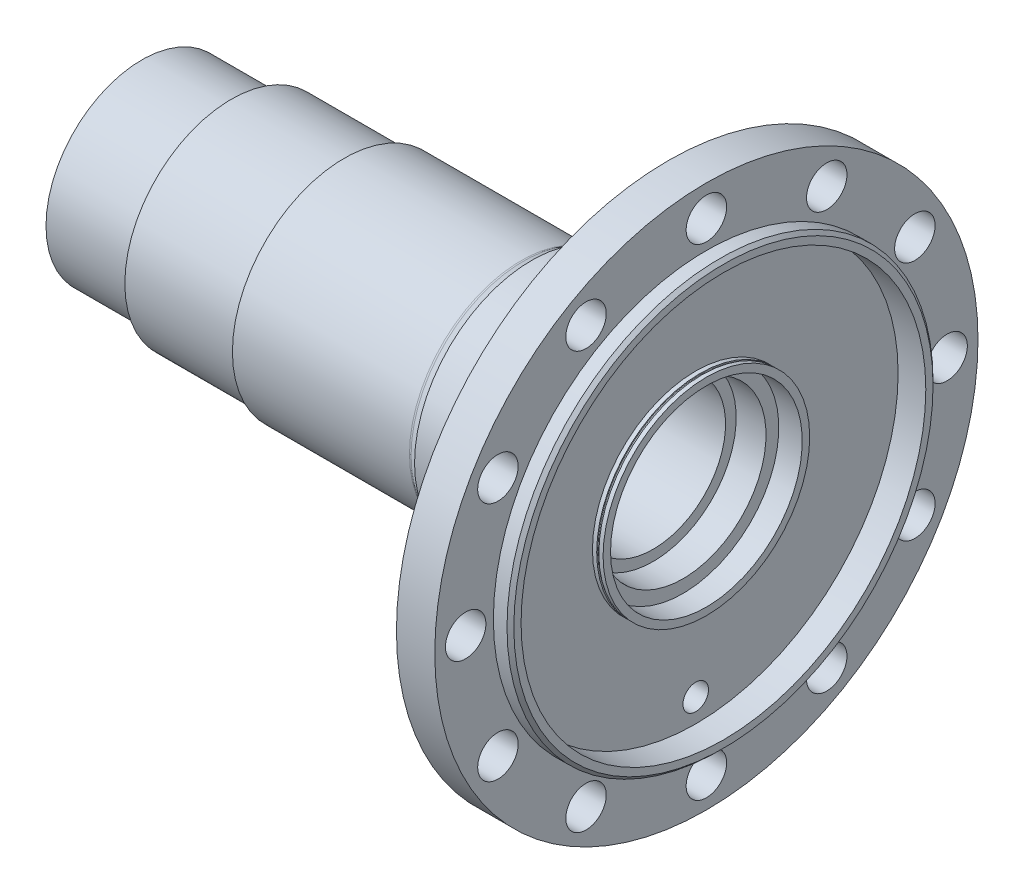
SolidWorks part; units mm, degrees
ref_plane "Спереди" through (0, 0, 0) normal (0, 0, 1) x (1, 0, 0)
ref_plane "Сверху" through (0, 0, 0) normal (0, 1, 0) x (1, 0, 0)
ref_plane "Справа" through (0, 0, 0) normal (1, 0, 0) x (0, 0, -1)
sketch "Эскиз1" plane through (0, 0, 0) normal (0, 0, 1) x (1, 0, 0)
  line L0 (0, 0) -> (273, 0)
  line L1 (0, 0) -> (0, 45)
  line L2 (0, 45) -> (42, 45)
  line L3 (42, 45) -> (42, 50)
  line L4 (42, 50) -> (95, 50)
  line L5 (95, 50) -> (95, 52.5)
  line L6 (95, 52.5) -> (178.134, 52.5)
  line L7 (179.134, 52.7679) -> (183, 55)
  line L8 (183, 55) -> (213, 55)
  line L9 (215, 57) -> (215, 60.7679)
  line L10 (215, 60.7679) -> (218, 62.5)
  line L11 (218, 62.5) -> (237, 62.5)
  line L12 (239, 64.5) -> (239, 100)
  line L13 (239, 100) -> (247, 100)
  line L14 (247, 100) -> (247, 127.5)
  line L15 (247, 127.5) -> (265, 127.5)
  line L16 (265, 127.5) -> (265, 100)
  line L17 (265, 100) -> (271.4, 100)
  line L18 (271.4, 100) -> (273, 98.4)
  line L19 (273, 98.4) -> (273, 0)
  arc A0 (178.134, 52.5) -> (179.134, 52.7679) centre (178.134, 54.5) ccw
  arc A1 (213, 55) -> (215, 57) centre (213, 57) ccw
  arc A2 (237, 62.5) -> (239, 64.5) centre (237, 64.5) ccw
revolve "Повернуть1" add sketch "Эскиз1" angle 360 about L0
sketch "Эскиз2" plane through (0, 0, 0) normal (0, 0, 1) x (1, 0, 0)
  line L0 (0, 0) -> (273, 0)
  line L1 (0, 0) -> (0, 31)
  line L2 (0, 31) -> (203.5, 31)
  line L3 (203.5, 31) -> (203.5, 34)
  line L4 (203.5, 34) -> (240, 34)
  line L5 (240, 34) -> (240, 39)
  line L6 (240, 39) -> (254, 39)
  line L7 (254, 39) -> (254, 45)
  line L8 (254, 45) -> (265, 45)
  line L9 (265, 45) -> (265, 95)
  line L10 (265, 95) -> (273, 95)
  line L11 (273, 95) -> (273, 0)
revolve "Вырез-Повернуть1" cut sketch "Эскиз2" angle 360 about L0
sketch "Эскиз3" plane through (0, 0, 0) normal (0, 0, 1) x (1, 0, 0)
  line L0 (0, 0) -> (273, 0) construction
  line L1 (260, 48.5) -> (262, 48.5)
  line L2 (262, 48.5) -> (262, 95)
  line L3 (262, 95) -> (260, 95)
  line L4 (260, 95) -> (260, 48.5)
revolve "Rear_recess_left" cut sketch "Эскиз3" angle 360 about L0
sketch "Эскиз4" plane through (0, 0, 0) normal (0, 0, 1) x (1, 0, 0)
  line L0 (0, 0) -> (273, 0) construction
  line L1 (263, 48) -> (263, 95)
  line L2 (263, 95) -> (262, 95)
  line L3 (262, 95) -> (262, 48)
  arc A0 (262, 48) -> (262.5, 47.5) centre (262.5, 48) ccw
  arc A1 (262.5, 47.5) -> (263, 48) centre (262.5, 48) ccw
revolve "Collar_groove_nominal" cut sketch "Эскиз4" angle 360 about L0
sketch "Эскиз5" plane through (0, 0, 0) normal (0, 0, 1) x (1, 0, 0)
  line L0 (0, 0) -> (273, 0) construction
  line L1 (263, 48.5) -> (265, 48.5)
  line L2 (265, 48.5) -> (265, 95)
  line L3 (265, 95) -> (263, 95)
  line L4 (263, 95) -> (263, 48.5)
revolve "Rear_recess_lip" cut sketch "Эскиз5" angle 360 about L0
sketch "Эскиз6" plane through (0, 0, 0) normal (1, 0, 0) x (0, 0, -1)
  circle A0 centre (0, 113) radius 9.5
extrude "Вырез-Вытянуть1" cut sketch "Эскиз6" along normal through all
sketch "Эскиз7" plane through (0, 0, 0) normal (1, 0, 0) x (0, 0, -1)
  circle A0 centre (-56.5, 97.8609) radius 9.5
extrude "Вырез-Вытянуть2" cut sketch "Эскиз7" along normal through all
sketch "Эскиз8" plane through (0, 0, 0) normal (1, 0, 0) x (0, 0, -1)
  circle A0 centre (-97.8609, 56.5) radius 9.5
extrude "Вырез-Вытянуть3" cut sketch "Эскиз8" along normal through all
sketch "Эскиз9" plane through (0, 0, 0) normal (1, 0, 0) x (0, 0, -1)
  circle A0 centre (-113, 0) radius 9.5
extrude "Вырез-Вытянуть4" cut sketch "Эскиз9" along normal through all
sketch "Эскиз10" plane through (0, 0, 0) normal (1, 0, 0) x (0, 0, -1)
  circle A0 centre (-97.8609, -56.5) radius 9.5
extrude "Вырез-Вытянуть5" cut sketch "Эскиз10" along normal through all
sketch "Эскиз11" plane through (0, 0, 0) normal (1, 0, 0) x (0, 0, -1)
  circle A0 centre (-56.5, -97.8609) radius 9.5
extrude "Вырез-Вытянуть6" cut sketch "Эскиз11" along normal through all
sketch "Эскиз12" plane through (0, 0, 0) normal (1, 0, 0) x (0, 0, -1)
  circle A0 centre (0, -113) radius 9.5
extrude "Вырез-Вытянуть7" cut sketch "Эскиз12" along normal through all
sketch "Эскиз13" plane through (0, 0, 0) normal (1, 0, 0) x (0, 0, -1)
  circle A0 centre (56.5, -97.8609) radius 9.5
extrude "Вырез-Вытянуть8" cut sketch "Эскиз13" along normal through all
sketch "Эскиз14" plane through (0, 0, 0) normal (1, 0, 0) x (0, 0, -1)
  circle A0 centre (97.8609, -56.5) radius 9.5
extrude "Вырез-Вытянуть9" cut sketch "Эскиз14" along normal through all
sketch "Эскиз15" plane through (0, 0, 0) normal (1, 0, 0) x (0, 0, -1)
  circle A0 centre (113, 0) radius 9.5
extrude "Вырез-Вытянуть10" cut sketch "Эскиз15" along normal through all
sketch "Эскиз16" plane through (0, 0, 0) normal (1, 0, 0) x (0, 0, -1)
  circle A0 centre (97.8609, 56.5) radius 9.5
extrude "Вырез-Вытянуть11" cut sketch "Эскиз16" along normal through all
sketch "Эскиз17" plane through (0, 0, 0) normal (1, 0, 0) x (0, 0, -1)
  circle A0 centre (56.5, 97.8609) radius 9.5
extrude "Вырез-Вытянуть12" cut sketch "Эскиз17" along normal through all
sketch "Эскиз18" plane through (0, 0, 0) normal (1, 0, 0) x (0, 0, -1)
  circle A0 centre (0, -84) radius 6
extrude "Вырез-Вытянуть13" cut sketch "Эскиз18" along normal through all
